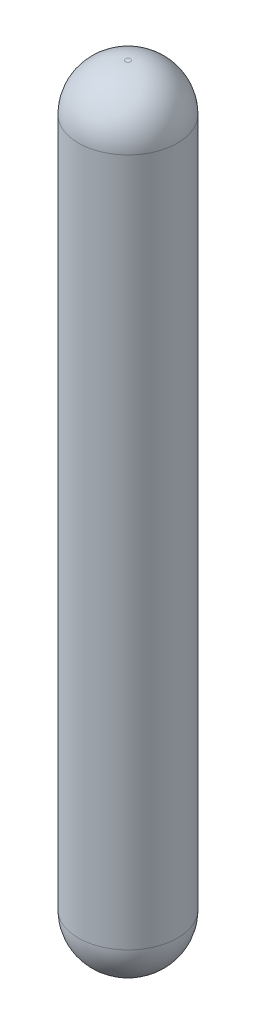
SolidWorks part; units mm, degrees
ref_plane "Front Plane" through (0, 0, 0) normal (0, 0, 1) x (1, 0, 0)
ref_plane "Top Plane" through (0, 0, 0) normal (0, 1, 0) x (1, 0, 0)
ref_plane "Right Plane" through (0, 0, 0) normal (1, 0, 0) x (0, 0, -1)
sketch "Sketch2" plane through (0, 0, 0) normal (0, 1, 0) x (1, 0, 0)
  circle A0 centre (0, 0) radius 3.8
  dimension "D1" = 7.6
extrude "Boss-Extrude1" add sketch "Sketch2" along normal blind 60
fillet "Fillet5" radius 3.6 2 edges at (0, 0, 3.8) (0, 60, 3.8)
